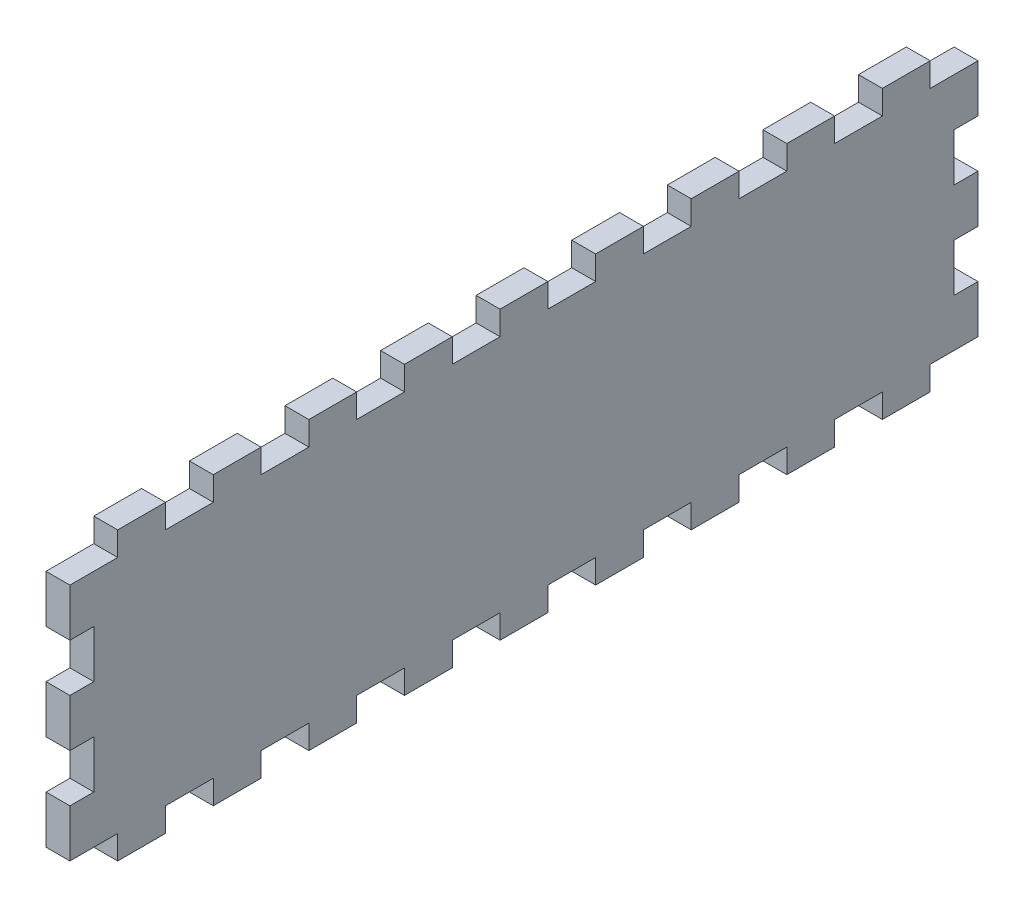
SolidWorks part; units mm, degrees
ref_plane "Front Plane" through (0, 0, 0) normal (0, 0, 1) x (1, 0, 0)
ref_plane "Top Plane" through (0, 0, 0) normal (0, 1, 0) x (1, 0, 0)
ref_plane "Right Plane" through (0, 0, 0) normal (1, 0, 0) x (0, 0, -1)
sketch "Sketch2" plane through (0, 0, 0) normal (1, 0, 0) x (0, 0, -1)
  line L6 (-30.0896, -3.3632) -> (-30.0896, 1.6368)
  line L7 (-30.0896, 1.6368) -> (-40.0896, 1.6368)
  line L8 (-40.0896, 1.6368) -> (-40.0896, -3.3632)
  line L9 (-40.0896, -3.3632) -> (-50.0896, -3.3632)
  line L10 (-50.0896, -3.3632) -> (-50.0896, 1.6368)
  line L11 (-50.0896, 1.6368) -> (-60.0896, 1.6368)
  line L12 (-60.0896, 1.6368) -> (-60.0896, -3.3632)
  line L13 (-60.0896, -3.3632) -> (-70.0896, -3.3632)
  line L14 (-70.0896, -3.3632) -> (-70.0896, 1.6368)
  line L15 (-70.0896, 1.6368) -> (-80.0896, 1.6368)
  line L16 (-80.0896, 1.6368) -> (-80.0896, -3.3632)
  line L17 (-80.0896, -3.3632) -> (-90.0896, -3.3632)
  line L18 (-90.0896, -3.3632) -> (-90.0896, 1.6368)
  line L19 (-90.0896, 1.6368) -> (-100.0896, 1.6368)
  line L20 (-100.0896, 1.6368) -> (-100.0896, -3.3632)
  line L21 (-100.0896, -3.3632) -> (-110.0896, -3.3632)
  line L22 (-110.0896, -3.3632) -> (-110.0896, 1.6368)
  line L23 (-110.0896, 1.6368) -> (-120.0896, 1.6368)
  line L24 (-120.0896, 1.6368) -> (-120.0896, -3.3632)
  line L25 (-120.0896, -3.3632) -> (-130.0896, -3.3632)
  line L26 (-130.0896, -3.3632) -> (-130.0896, 1.6368)
  line L27 (-130.0896, 1.6368) -> (-140.0896, 1.6368)
  line L28 (-140.0896, 1.6368) -> (-140.0896, -3.3632)
  line L29 (-140.0896, -3.3632) -> (-150.0896, -3.3632)
  line L30 (-150.0896, -3.3632) -> (-150.0896, 1.6368)
  line L31 (-150.0896, 1.6368) -> (-160.0896, 1.6368)
  line L32 (-160.0896, 1.6368) -> (-160.0896, -3.3632)
  line L33 (-160.0896, -3.3632) -> (-170.0896, -3.3632)
  line L34 (-170.0896, -3.3632) -> (-170.0896, 1.6368)
  line L35 (-170.0896, 1.6368) -> (-180.0896, 1.6368)
  line L36 (-180.0896, 1.6368) -> (-180.0896, -3.3632)
  line L37 (-180.0896, -3.3632) -> (-190.0896, -3.3632)
  line L38 (-190.0896, -3.3632) -> (-190.0896, 1.6368)
  line L39 (-190.0896, 1.6368) -> (-200.0896, 1.6368)
  line L40 (-200.0896, 1.6368) -> (-200.0896, -3.3632)
  line L63 (-200.0896, 17.5016) -> (-30.0896, 17.5016) construction
  line L64 (-115.0896, 17.5016) -> (-115.0896, 22.1756) construction
  line L89 (-200.0896, -3.3632) -> (-210.0896, -3.3632)
  line L137 (-210.0896, -3.3632) -> (-210.0896, -13.3632)
  line L198 (-210.0896, -13.3632) -> (-205.0896, -13.3632)
  line L199 (-205.0896, -13.3632) -> (-205.0896, -23.3632)
  line L264 (-205.0896, -23.3632) -> (-210.0896, -23.3632)
  line L269 (-210.0896, -23.3632) -> (-210.0896, -33.3632)
  line L270 (-210.0896, -33.3632) -> (-205.0896, -33.3632)
  line L271 (-205.0896, -33.3632) -> (-205.0896, -43.3632)
  line L272 (-205.0896, -43.3632) -> (-210.0896, -43.3632)
  line L273 (-210.0896, -43.3632) -> (-210.0896, -53.3632)
  line L274 (-210.0896, -53.3632) -> (-200.0896, -53.3632)
  line L275 (-227.2315, -3.3632) -> (-227.2315, -53.3632) construction
  line L276 (-227.2315, -28.3632) -> (-233.7306, -28.3632) construction
  line L277 (-200.0896, -58.3632) -> (-200.0896, -53.3632)
  line L278 (-190.0896, -58.3632) -> (-200.0896, -58.3632)
  line L279 (-190.0896, -53.3632) -> (-190.0896, -58.3632)
  line L280 (-180.0896, -53.3632) -> (-190.0896, -53.3632)
  line L281 (-180.0896, -58.3632) -> (-180.0896, -53.3632)
  line L282 (-170.0896, -58.3632) -> (-180.0896, -58.3632)
  line L283 (-170.0896, -53.3632) -> (-170.0896, -58.3632)
  line L284 (-160.0896, -53.3632) -> (-170.0896, -53.3632)
  line L285 (-160.0896, -58.3632) -> (-160.0896, -53.3632)
  line L286 (-150.0896, -58.3632) -> (-160.0896, -58.3632)
  line L287 (-150.0896, -53.3632) -> (-150.0896, -58.3632)
  line L288 (-140.0896, -53.3632) -> (-150.0896, -53.3632)
  line L289 (-140.0896, -58.3632) -> (-140.0896, -53.3632)
  line L290 (-130.0896, -58.3632) -> (-140.0896, -58.3632)
  line L291 (-130.0896, -53.3632) -> (-130.0896, -58.3632)
  line L292 (-120.0896, -53.3632) -> (-130.0896, -53.3632)
  line L293 (-120.0896, -58.3632) -> (-120.0896, -53.3632)
  line L294 (-110.0896, -58.3632) -> (-120.0896, -58.3632)
  line L295 (-110.0896, -53.3632) -> (-110.0896, -58.3632)
  line L296 (-100.0896, -53.3632) -> (-110.0896, -53.3632)
  line L297 (-100.0896, -58.3632) -> (-100.0896, -53.3632)
  line L298 (-90.0896, -58.3632) -> (-100.0896, -58.3632)
  line L299 (-90.0896, -53.3632) -> (-90.0896, -58.3632)
  line L300 (-80.0896, -53.3632) -> (-90.0896, -53.3632)
  line L301 (-80.0896, -58.3632) -> (-80.0896, -53.3632)
  line L302 (-70.0896, -58.3632) -> (-80.0896, -58.3632)
  line L303 (-70.0896, -53.3632) -> (-70.0896, -58.3632)
  line L304 (-60.0896, -53.3632) -> (-70.0896, -53.3632)
  line L305 (-60.0896, -58.3632) -> (-60.0896, -53.3632)
  line L306 (-50.0896, -58.3632) -> (-60.0896, -58.3632)
  line L307 (-50.0896, -53.3632) -> (-50.0896, -58.3632)
  line L308 (-40.0896, -53.3632) -> (-50.0896, -53.3632)
  line L309 (-40.0896, -58.3632) -> (-40.0896, -53.3632)
  line L310 (-30.0896, -58.3632) -> (-40.0896, -58.3632)
  line L311 (-30.0896, -53.3632) -> (-30.0896, -58.3632)
  line L312 (-20.0896, -53.3632) -> (-30.0896, -53.3632)
  line L313 (-20.0896, -43.3632) -> (-20.0896, -53.3632)
  line L314 (-25.0896, -43.3632) -> (-20.0896, -43.3632)
  line L315 (-25.0896, -33.3632) -> (-25.0896, -43.3632)
  line L316 (-20.0896, -33.3632) -> (-25.0896, -33.3632)
  line L317 (-20.0896, -23.3632) -> (-20.0896, -33.3632)
  line L318 (-25.0896, -23.3632) -> (-20.0896, -23.3632)
  line L319 (-25.0896, -13.3632) -> (-25.0896, -23.3632)
  line L320 (-20.0896, -13.3632) -> (-25.0896, -13.3632)
  line L321 (-20.0896, -3.3632) -> (-20.0896, -13.3632)
  line L322 (-30.0896, -3.3632) -> (-20.0896, -3.3632)
  point P100 (-20.0896, -28.3632)
  dimension "D1" = 10
  dimension "D2" = 10
  dimension "D3" = 5
  dimension "D4" = 10
  dimension "D5" = 10
  dimension "D6" = 10
  dimension "D8" = 5
  dimension "D9" = 190
  dimension "D10" = 60
  dimension "D7" = 10
extrude "Boss-Extrude3" add sketch "Sketch2" along normal blind 5 contours L38 L39 L40 L89 L137 L198 L199 L264 L269 L270 L271 L272 L273 L274 L277 L278 L279 L280 L281 L282 L283 L284 L285 L286 L287 L288 L289 L290 L291 L292 L293 L294 L295 L296 L297 L298 L299 L300 L301 L302 L303 L304 L305 L306 L307 L308 L309 L310 L311 L312 L313 L314 L315 L316 L317 L318 L319 L320 L321 L322 L6 L7 L8 L9 L10 L11 L12 L13 L14 L15 L16 L17 L18 L19 L20 L21 L22 L23 L24 L25 L26 L27 L28 L29 L30 L31 L32 L33 L34 L35 L36 L37
